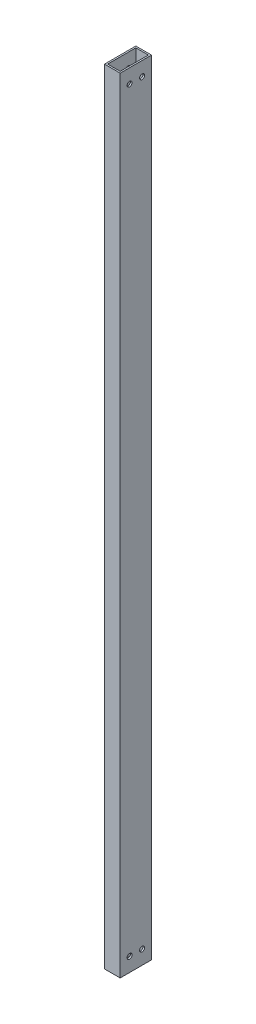
SolidWorks part; units mm, degrees
material "Acero al carbono no aleado"
ref_plane "Alzado" through (0, 0, 0) normal (0, 0, 1) x (1, 0, 0)
ref_plane "Planta" through (0, 0, 0) normal (0, 1, 0) x (1, 0, 0)
ref_plane "Vista lateral" through (0, 0, 0) normal (1, 0, 0) x (0, 0, -1)
sketch "Croquis1" plane through (0, 0, 0) normal (1, 0, 0) x (0, 0, -1)
  line L1 (0, 0) -> (-40, 0)
  line L2 (0, 0) -> (0, 1000)
  line L3 (0, 1000) -> (-40, 1000)
  line L4 (-40, 0) -> (-40, 1000)
  dimension "D1" = 1000
  dimension "D2" = 40
extrude "Saliente-Extruir1" add sketch "Croquis1" along normal blind 20
sketch "Croquis2" plane through (0, 1000, 0) normal (0, 1, 0) x (1, 0, 0)
  line L0 (20, -40) -> (0, -40) construction
  line L1 (2, -2) -> (18, -2)
  line L2 (2, -2) -> (2, -38)
  line L3 (2, -38) -> (18, -38)
  line L4 (18, -2) -> (18, -38)
  line L5 (2, -2) -> (18, -38) construction
  line L6 (2, -38) -> (18, -2) construction
  line L7 (20, 0) -> (0, 0) construction
  line L8 (0, 0) -> (0, -40) construction
  line L9 (20, 0) -> (20, -40) construction
  point P0 (10, -20)
  dimension "D1" = 2
  dimension "D2" = 2
  dimension "D3" = 2
  dimension "D4" = 2
extrude "Cortar-Extruir1" cut sketch "Croquis2" against normal blind 1000
sketch "Croquis3" plane through (0, 0, 0) normal (-1, 0, 0) x (0, 0, 1)
  line L1 (0, 1000) -> (40, 1000) construction
  line L3 (40, 1000) -> (40, 0) construction
  line L4 (0, 0) -> (0, 1000) construction
  line L5 (40, 500) -> (-16.7749, 500) construction
  circle A1 centre (12, 982) radius 3.175
  circle A2 centre (28, 982) radius 3.175
  circle A3 centre (28, 18) radius 3.175
  circle A4 centre (12, 18) radius 3.175
  dimension "D3" = 12
  dimension "D1" = 18
  dimension "D2" = 18
  dimension "D4" = 12
  dimension "D5" = 16
extrude "Cortar-Extruir2" cut sketch "Croquis3" against normal blind 1000
